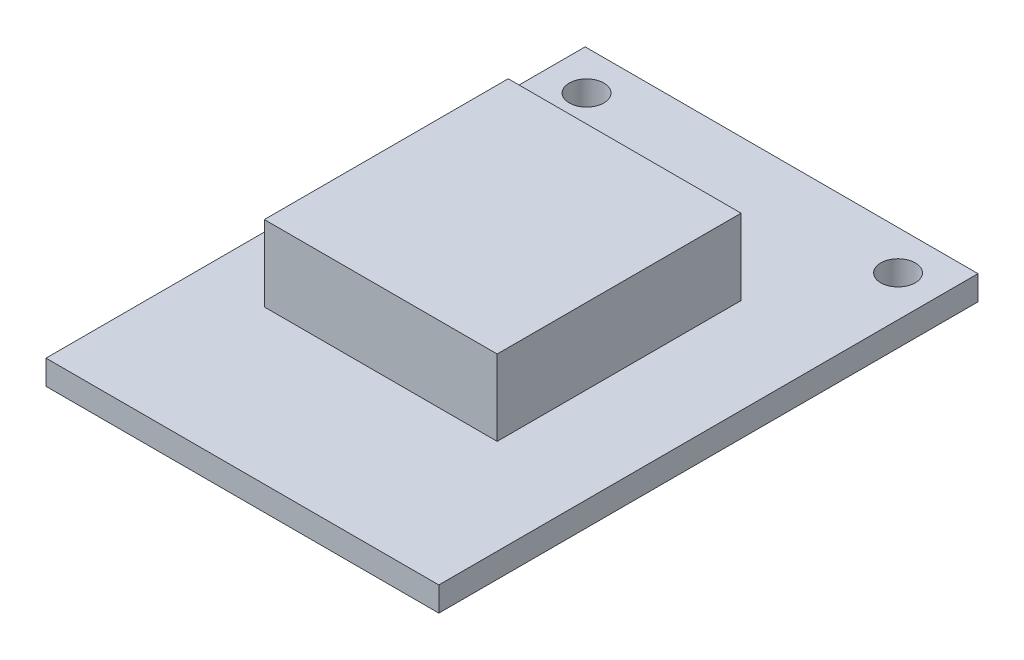
SolidWorks part; units mm, degrees
ref_plane "Front Plane" through (0, 0, 0) normal (0, 0, 1) x (1, 0, 0)
ref_plane "Top Plane" through (0, 0, 0) normal (0, 1, 0) x (1, 0, 0)
ref_plane "Right Plane" through (0, 0, 0) normal (1, 0, 0) x (0, 0, -1)
sketch "Sketch1" plane through (0, 0, 0) normal (0, 1, 0) x (1, 0, 0)
  line L1 (-12.75, -17.5) -> (12.75, -17.5)
  line L2 (-12.75, -17.5) -> (-12.75, 17.5)
  line L3 (-12.75, 17.5) -> (12.75, 17.5)
  line L4 (12.75, -17.5) -> (12.75, 17.5)
  line L5 (-12.75, -17.5) -> (12.75, 17.5) construction
  line L6 (-12.75, 17.5) -> (12.75, -17.5) construction
  point P0 (0, 0)
  dimension "D1" = 25.5
  dimension "D2" = 35
extrude "Boss-Extrude1" add sketch "Sketch1" along normal blind 1.5875
sketch "Sketch2" plane through (0, 1.5875, 0) normal (0, 1, 0) x (1, 0, 0)
  line L1 (-8.5421, 8.2962) -> (6.5743, 8.2962)
  line L2 (-8.5421, 8.2962) -> (-8.5421, -7.5359)
  line L3 (-8.5421, -7.5359) -> (6.5743, -7.5359)
  line L4 (6.5743, 8.2962) -> (6.5743, -7.5359)
extrude "Boss-Extrude2" add sketch "Sketch2" along normal blind 4.9125
sketch "Sketch3" plane through (0, 1.5875, 0) normal (0, 1, 0) x (1, 0, 0)
  line L0 (8.9875, 14.9494) -> (-8.9875, 14.9494) construction
  line L1 (0, 14.9494) -> (0, 17.5) construction
  line L2 (12.75, 17.5) -> (-12.75, 17.5) construction
  line L3 (-10.11, 16.072) -> (10.11, 16.072) construction
  circle A0 centre (-10.11, 14.9494) radius 1.1226
  circle A1 centre (10.11, 14.9494) radius 1.1226
  point P10 (-10.1197, 14.9204)
  point P13 (-10.11, 14.9494)
extrude "Cut-Extrude1" cut sketch "Sketch3" against normal up to next
